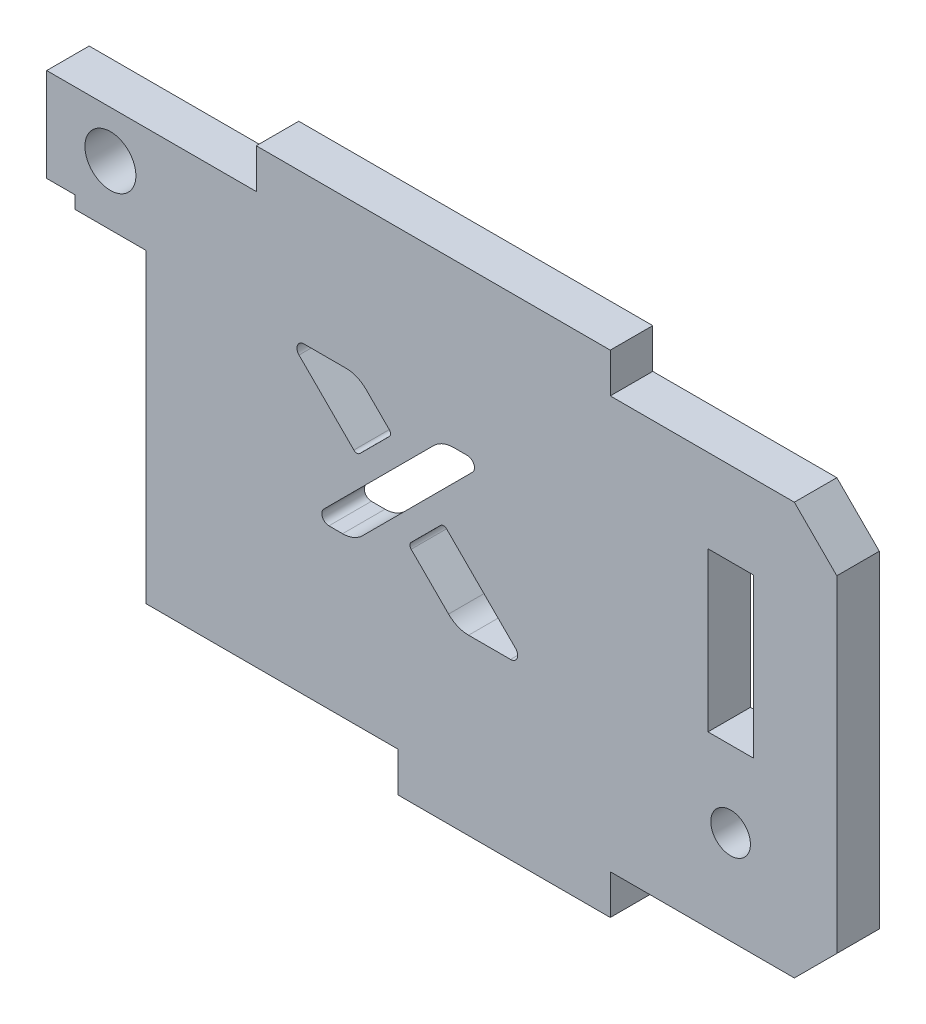
SolidWorks part; units mm, degrees
ref_plane "前视基准面" through (0, 0, 0) normal (0, 0, 1) x (1, 0, 0)
ref_plane "上视基准面" through (0, 0, 0) normal (0, 1, 0) x (1, 0, 0)
ref_plane "右视基准面" through (0, 0, 0) normal (1, 0, 0) x (0, 0, -1)
sketch "草图1" plane through (0, 0, 0) normal (0, 0, 1) x (1, 0, 0)
  line L1 (-48.1127, -4.8637) -> (-43.2391, 0.01)
  line L3 (-42.8148, 0.01) -> (-40.7391, -2.0658)
  line L5 (-40.7391, -2.49) -> (-43.3805, -5.1315)
  line L12 (-64.8, -6.08) -> (-64.8, 5.92)
  line L13 (-64.8, 13.92) -> (-67.8, 13.92)
  line L14 (-67.8, 13.92) -> (-70.8, 10.92)
  line L15 (-70.8, 10.92) -> (-70.8, -12.18)
  line L16 (-70.8, -12.18) -> (-67.8, -15.18)
  line L17 (-67.8, -15.18) -> (-64.8, -15.18)
  line L19 (-44.7947, -5.7173) -> (-47.7592, -5.7173)
  line L21 (-37.3094, -3.3741) -> (-45.0625, 4.3789)
  line L23 (-42.3303, 4.6467) -> (-34.5772, -3.1063)
  line L25 (-34.9308, -3.9599) -> (-35.8952, -3.9599)
  line L27 (-44.7089, 5.2325) -> (-43.7445, 5.2325)
  line L32 (-32.8199, 5.4292) -> (-36.6935, 1.5555)
  line L33 (-36.1379, 6.2827) -> (-33.1734, 6.2827)
  line L34 (-39.1935, 4.0555) -> (-37.5521, 5.697)
  line L35 (-37.1178, 1.5555) -> (-39.1935, 3.6313)
  line L37 (61.8, -6.0769) -> (61.8, 5.9231)
  line L76 (-61.8, 5.92) -> (-61.8, -6.08)
  line L77 (-61.8, -6.08) -> (-64.8, -6.08)
  line L79 (-64.8, -15.18) -> (-54.8, -15.18)
  line L80 (-54.8, -15.18) -> (-54.8, -17.98)
  line L81 (-54.8, -17.98) -> (-39.8, -17.98)
  line L82 (-39.8, -17.98) -> (-39.8, -15.18)
  line L83 (-39.8, -15.18) -> (-22, -15.18)
  line L84 (-22, -15.18) -> (-22, 3.32)
  line L85 (-22, 3.32) -> (-17, 3.32)
  line L86 (-17, 3.32) -> (-17, 0.32)
  line L87 (-17, 0.32) -> (17, 0.32)
  line L88 (17, 0.32) -> (17, 3.32)
  line L89 (17, 3.32) -> (22, 3.32)
  line L90 (22, 3.32) -> (22, -15.18)
  line L91 (22, -15.18) -> (39.8, -15.18)
  line L92 (39.8, -15.18) -> (39.8, -17.98)
  line L93 (39.8, -17.98) -> (54.8, -17.98)
  line L94 (54.8, -17.98) -> (54.8, -15.18)
  line L95 (54.8, -15.18) -> (67.8, -15.18)
  line L96 (67.8, -15.18) -> (70.8, -12.18)
  line L97 (70.8, -12.18) -> (70.8, 10.92)
  line L98 (70.8, 10.92) -> (67.8, 13.92)
  line L99 (67.8, 13.92) -> (54.8, 13.92)
  line L100 (54.8, 13.92) -> (54.8, 16.72)
  line L101 (54.8, 16.72) -> (29.8, 16.72)
  line L102 (29.8, 16.72) -> (29.8, 13.92)
  line L103 (29.8, 13.92) -> (10, 13.92)
  line L104 (10, 13.92) -> (10, 16.72)
  line L105 (10, 16.72) -> (-10, 16.72)
  line L106 (-10, 16.72) -> (-10, 13.92)
  line L107 (-10, 13.92) -> (-29.8, 13.92)
  line L108 (-29.8, 13.92) -> (-29.8, 16.72)
  line L109 (-29.8, 16.72) -> (-54.8, 16.72)
  line L110 (-54.8, 16.72) -> (-54.8, 13.92)
  line L111 (-54.8, 13.92) -> (-64.8, 13.92)
  line L113 (-64.8, 5.92) -> (-61.8, 5.92)
  line L115 (61.8, 5.9231) -> (64.8, 5.9231)
  line L117 (64.8, 5.9231) -> (64.8, -6.0769)
  line L119 (64.8, -6.0769) -> (61.8, -6.0769)
  line L121 (42.3303, 4.6467) -> (34.5772, -3.1063)
  line L123 (34.9308, -3.9599) -> (35.8952, -3.9599)
  line L125 (37.3094, -3.3741) -> (45.0625, 4.3789)
  line L127 (44.7089, 5.2325) -> (43.7445, 5.2325)
  line L129 (48.1127, -4.8637) -> (43.2391, 0.01)
  line L131 (42.8148, 0.01) -> (40.7391, -2.0658)
  line L133 (40.7391, -2.49) -> (43.3805, -5.1315)
  line L135 (44.7947, -5.7173) -> (47.7592, -5.7173)
  line L137 (39.1935, 4.0555) -> (37.5521, 5.697)
  line L139 (32.8199, 5.4292) -> (36.6935, 1.5555)
  line L141 (36.1379, 6.2827) -> (33.1734, 6.2827)
  line L143 (37.1178, 1.5555) -> (39.1935, 3.6313)
  circle A1 centre (-19.5, 10.6369) radius 1.8
  circle A3 centre (19.5, 10.6369) radius 1.8
  arc A5 (-44.7947, -5.7173) -> (-43.3805, -5.1315) centre (-44.7947, -3.7173) ccw
  arc A7 (-48.1127, -4.8637) -> (-47.7592, -5.7173) centre (-47.7592, -5.2173) ccw
  arc A9 (-42.8148, 0.01) -> (-43.2391, 0.01) centre (-43.027, -0.2022) ccw
  arc A11 (-40.7391, -2.49) -> (-40.7391, -2.0658) centre (-40.9512, -2.2779) ccw
  arc A13 (-37.3094, -3.3741) -> (-35.8952, -3.9599) centre (-35.8952, -1.9599) ccw
  arc A15 (-34.9308, -3.9599) -> (-34.5772, -3.1063) centre (-34.9308, -3.4599) ccw
  arc A17 (-44.7089, 5.2325) -> (-45.0625, 4.3789) centre (-44.7089, 4.7325) ccw
  arc A19 (-42.3303, 4.6467) -> (-43.7445, 5.2325) centre (-43.7445, 3.2325) ccw
  arc A24 (-37.1178, 1.5555) -> (-36.6935, 1.5555) centre (-36.9056, 1.7677) ccw
  arc A25 (-32.8199, 5.4292) -> (-33.1734, 6.2827) centre (-33.1734, 5.7827) ccw
  arc A26 (-36.1379, 6.2827) -> (-37.5521, 5.697) centre (-36.1379, 4.2827) ccw
  arc A27 (-39.1935, 4.0555) -> (-39.1935, 3.6313) centre (-38.9814, 3.8434) ccw
  arc A29 (34.5772, -3.1063) -> (34.9308, -3.9599) centre (34.9308, -3.4599) ccw
  arc A31 (35.8952, -3.9599) -> (37.3094, -3.3741) centre (35.8952, -1.9599) ccw
  arc A33 (43.7445, 5.2325) -> (42.3303, 4.6467) centre (43.7445, 3.2325) ccw
  arc A35 (45.0625, 4.3789) -> (44.7089, 5.2325) centre (44.7089, 4.7325) ccw
  arc A37 (43.2391, 0.01) -> (42.8148, 0.01) centre (43.027, -0.2022) ccw
  arc A39 (40.7391, -2.0658) -> (40.7391, -2.49) centre (40.9512, -2.2779) ccw
  arc A41 (47.7592, -5.7173) -> (48.1127, -4.8637) centre (47.7592, -5.2173) ccw
  arc A43 (43.3805, -5.1315) -> (44.7947, -5.7173) centre (44.7947, -3.7173) ccw
  arc A45 (33.1734, 6.2827) -> (32.8199, 5.4292) centre (33.1734, 5.7827) ccw
  arc A47 (37.5521, 5.697) -> (36.1379, 6.2827) centre (36.1379, 4.2827) ccw
  arc A49 (39.1935, 3.6313) -> (39.1935, 4.0555) centre (38.9814, 3.8434) ccw
  arc A51 (36.6935, 1.5555) -> (37.1178, 1.5555) centre (36.9056, 1.7677) ccw
extrude "凸台-拉伸1" add sketch "草图1" along normal blind 3
sketch "草图3" plane through (0, 0, 0) normal (0, 0, -1) x (-1, 0, 0)
  line L0 (17, 0.32) -> (-17, 0.32) construction
  line L1 (17, 0.32) -> (-17, 0.32)
  line L2 (-17, 0.32) -> (-17, 3.32) construction
  line L3 (-17, 0.32) -> (-17, 3.32)
  line L4 (17, 3.32) -> (17, 0.32) construction
  line L5 (17, 3.32) -> (17, 0.32)
  line L6 (-17, 3.32) -> (17, 3.32)
extrude "切除-拉伸1" cut sketch "草图3" against normal blind 10
sketch "草图4" plane through (0, 0, 0) normal (0, 0, -1) x (-1, 0, 0)
  line L1 (22, 3.32) -> (-22, 3.32) construction
  line L2 (19, 3.32) -> (19, 5.32)
  line L3 (19, 5.32) -> (-19, 5.32)
  line L6 (-19, 3.32) -> (-19, 5.32)
  line L7 (-19, 3.32) -> (19, 3.32)
extrude "切除-拉伸2" cut sketch "草图4" against normal blind 10
sketch "草图5" plane through (-19, 0, 0) normal (1, 0, 0) x (0, 0, -1)
  line L4 (-3, 3.32) -> (0, 3.32)
  line L5 (0, 3.32) -> (0, 5.32)
  line L6 (0, 5.32) -> (-3, 5.32)
  line L7 (-3, 5.32) -> (-3, 3.32)
  line L8 (-3, 3.32) -> (0, 3.32)
  line L9 (0, 3.32) -> (0, 5.32)
  line L10 (0, 5.32) -> (-3, 5.32)
  line L11 (-3, 5.32) -> (-3, 3.32)
  dimension "D1" = 0
extrude "凸台-拉伸2" add sketch "草图5" along normal blind 2
sketch "草图6" plane through (19, 0, 0) normal (-1, 0, 0) x (0, 0, 1)
  line L4 (3, 5.32) -> (0, 5.32)
  line L5 (0, 5.32) -> (0, 3.32)
  line L6 (0, 3.32) -> (3, 3.32)
  line L7 (3, 3.32) -> (3, 5.32)
  line L8 (3, 5.32) -> (0, 5.32)
  line L9 (0, 5.32) -> (0, 3.32)
  line L10 (0, 3.32) -> (3, 3.32)
  line L11 (3, 3.32) -> (3, 5.32)
  dimension "D1" = 0
extrude "凸台-拉伸3" add sketch "草图6" along normal blind 2
sketch "草图7" plane through (0, 5.32, 0) normal (0, -1, 0) x (1, 0, 0)
  line L4 (-17, 0) -> (17, 0)
  line L5 (17, 0) -> (17, 3)
  line L6 (17, 3) -> (-17, 3)
  line L7 (-17, 3) -> (-17, 0)
  line L8 (-17, 0) -> (17, 0)
  line L9 (17, 0) -> (17, 3)
  line L10 (17, 3) -> (-17, 3)
  line L11 (-17, 3) -> (-17, 0)
  dimension "D1" = 0
extrude "切除-拉伸3" cut sketch "草图7" against normal blind 2
sketch "草图8" plane through (22, 0, 0) normal (-1, 0, 0) x (0, 0, 1)
  line L1 (3, -12.18) -> (0, -12.18)
  line L2 (0, -12.18) -> (0, -2.18)
  line L3 (0, 3.32) -> (0, -15.18) construction
  line L4 (0, 3.32) -> (0, -15.18)
  line L5 (0, -15.18) -> (3, -15.18)
  line L6 (3, -15.18) -> (3, 3.32)
  line L7 (3, 3.32) -> (0, 3.32)
  line L10 (3, -12.18) -> (3, -2.18)
  line L12 (0, -2.18) -> (3, -2.18)
  line L13 (3, -2.18) -> (3, -12.18)
  line M5 (0, 3.32) -> (0, -15.18)
  line M7 (3, -15.18) -> (3, 3.32)
  dimension "D1" = 0
extrude "凸台-拉伸4" add sketch "草图8" along normal blind 5 contours L12 L1 M5 M7
ref_plane "基准面1" through (0, 0, 0) normal (-1, 0, 0) x (0, 0, 1)
mirror "镜向1" about plane through (0, 0, 0) normal (-1, 0, 0) of "凸台-拉伸4"
sketch "草图9" plane through (0, -12.18, 0) normal (0, -1, 0) x (1, 0, 0)
  line L4 (-22, 3) -> (-22, 0)
  line L5 (-22, 0) -> (-17, 0)
  line L6 (-17, 0) -> (-17, 3)
  line L7 (-17, 3) -> (-22, 3)
  line L8 (-22, 3) -> (-22, 0)
  line L9 (-22, 0) -> (-17, 0)
  line L10 (-17, 0) -> (-17, 3)
  line L11 (-17, 3) -> (-22, 3)
  line L12 (22, 0) -> (22, 3)
  line L13 (22, 3) -> (17, 3)
  line L14 (17, 3) -> (17, 0)
  line L15 (17, 0) -> (22, 0)
  line L16 (22, 0) -> (22, 3)
  line L17 (22, 3) -> (17, 3)
  line L18 (17, 3) -> (17, 0)
  line L19 (17, 0) -> (22, 0)
  dimension "D1" = 0
  dimension "D2" = 0
extrude "切除-拉伸4" cut sketch "草图9" against normal blind 2
sketch "草图10" plane through (0, 0, 0) normal (0, 0, -1) x (-1, 0, 0)
  line L1 (17, 7.32) -> (-17, 7.32) construction
  line L2 (-15, 7.32) -> (-15, 18.7274)
  line L3 (-15, 18.7274) -> (81.7235, 18.7274)
  line L4 (81.7235, 18.7274) -> (81.7235, -24.7971)
  line L5 (81.7235, -24.7971) -> (-15, -24.7971)
  line L6 (-15, -24.7971) -> (-15, 7.32)
extrude "切除-拉伸5" cut sketch "草图10" against normal blind 10
sketch "草图11" plane through (17, 0, 0) normal (-1, 0, 0) x (0, 0, 1)
  line L4 (0, -2.18) -> (0, -10.18)
  line L5 (0, -10.18) -> (3, -10.18)
  line L6 (3, -10.18) -> (3, -2.18)
  line L7 (3, -2.18) -> (0, -2.18)
  line L8 (0, -2.18) -> (0, -10.18)
  line L9 (0, -10.18) -> (3, -10.18)
  line L10 (3, -10.18) -> (3, -2.18)
  line L11 (3, -2.18) -> (0, -2.18)
  dimension "D1" = 0
extrude "切除-拉伸6" cut sketch "草图11" against normal up to surface (5 mm away) up to face at (22, -12.68, 1.5)
sketch "草图12" plane through (0, 0, 0) normal (0, 0, -1) x (-1, 0, 0)
  line L0 (-61.8, 5.9231) -> (-61.8, -6.0769) construction
  line L1 (-61.8, 5.9231) -> (-61.8, -6.0769)
  line L2 (-61.8, -6.0769) -> (-64.8, -6.0769) construction
  line L3 (-61.8, -6.0769) -> (-64.8, -6.0769)
  line L4 (-64.8, -6.0769) -> (-64.8, 5.9231) construction
  line L5 (-64.8, -6.0769) -> (-64.8, 5.9231)
  line L6 (-64.8, 5.9231) -> (-61.8, 5.9231) construction
  line L7 (-64.8, 5.9231) -> (-61.8, 5.9231)
  line L8 (-61.7, 6.0231) -> (-61.7, -6.1769)
  line L9 (-61.7, -6.1769) -> (-64.9, -6.1769)
  line L10 (-64.9, -6.1769) -> (-64.9, 6.0231)
  line L11 (-64.9, 6.0231) -> (-61.7, 6.0231)
  dimension "D1" = 0.1
extrude "切除-拉伸7" cut sketch "草图12" against normal blind 10
sketch "草图13" plane through (0, -6.1769, 0) normal (0, 1, 0) x (1, 0, 0)
  line L4 (64.9, -3) -> (64.9, 0)
  line L5 (64.9, 0) -> (61.7, 0)
  line L6 (61.7, 0) -> (61.7, -3)
  line L7 (61.7, -3) -> (64.9, -3)
  line L8 (64.9, -3) -> (64.9, 0)
  line L9 (64.9, 0) -> (61.7, 0)
  line L10 (61.7, 0) -> (61.7, -3)
  line L11 (61.7, -3) -> (64.9, -3)
  dimension "D1" = 0
extrude "凸台-拉伸5" add sketch "草图13" along normal blind 3
sketch "草图14" plane through (0, 6.0231, 0) normal (0, -1, 0) x (1, 0, 0)
  line L4 (61.7, 3) -> (61.7, 0)
  line L5 (61.7, 0) -> (64.9, 0)
  line L6 (64.9, 0) -> (64.9, 3)
  line L7 (64.9, 3) -> (61.7, 3)
  line L8 (61.7, 3) -> (61.7, 0)
  line L9 (61.7, 0) -> (64.9, 0)
  line L10 (64.9, 0) -> (64.9, 3)
  line L11 (64.9, 3) -> (61.7, 3)
  dimension "D1" = 0
extrude "切除-拉伸8" cut sketch "草图14" against normal blind 3
sketch "草图15" plane through (0, 9.0231, 0) normal (0, -1, 0) x (1, 0, 0)
  line L4 (64.9, 3) -> (61.7, 3)
  line L5 (61.7, 3) -> (61.7, 0)
  line L6 (61.7, 0) -> (64.9, 0)
  line L7 (64.9, 0) -> (64.9, 3)
  line L8 (64.9, 3) -> (61.7, 3)
  line L9 (61.7, 3) -> (61.7, 0)
  line L10 (61.7, 0) -> (64.9, 0)
  line L11 (64.9, 0) -> (64.9, 3)
  dimension "D1" = 0
extrude "凸台-拉伸6" add sketch "草图15" along normal blind 1
extrude "切除-拉伸9" cut sketch "草图16" against normal blind 3 contours A0
sketch "草图16" plane through (-133.9432, 43.3273, 0) normal (0, 0, -1) x (-1, 0, 0)
  line L1 (-195.7432, -53.282) -> (-198.7432, -53.282)
  line L3 (-195.7432, -50.482) -> (-198.7432, -50.482)
  line L4 (-195.7432, -50.482) -> (-196.2197, -50.9268)
  line L5 (-198.2666, -52.8373) -> (-198.7432, -53.282)
  circle A0 centre (-197.2432, -51.882) radius 1.4
extrude "切除-拉伸10" cut sketch "草图17" against normal blind 10
sketch "草图17" plane through (-133.9432, 43.3273, 0) normal (0, 0, -1) x (-1, 0, 0)
  line L1 (-155.9432, -36.9011) -> (-150.9432, -36.9011)
  line L3 (-150.9432, -40.0073) -> (-155.9432, -40.0073)
  line L5 (-150.9432, -36.9011) -> (-150.9432, -40.0073)
  line L6 (-155.9432, -36.9011) -> (-155.9432, -40.0073)
